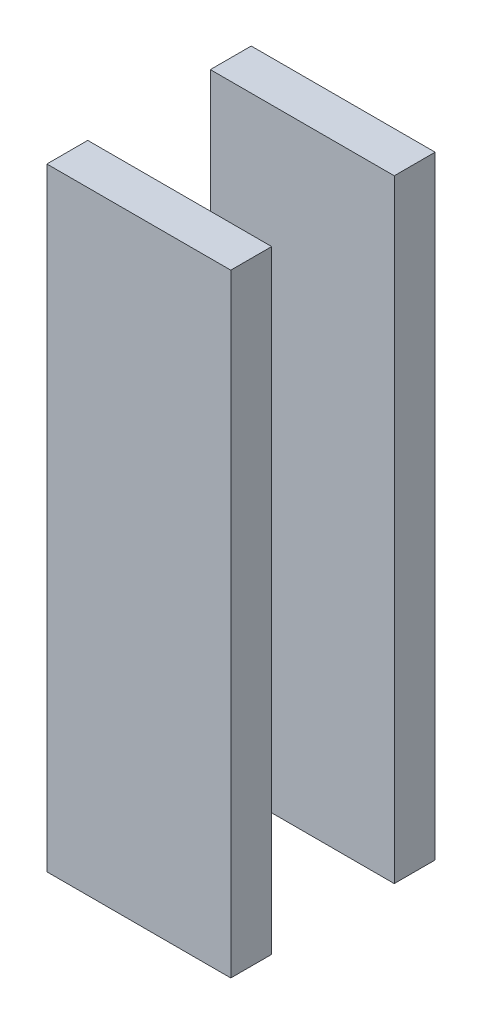
SolidWorks part; units mm, degrees
ref_plane "前视基准面" through (0, 0, 0) normal (0, 0, 1) x (1, 0, 0)
ref_plane "上视基准面" through (0, 0, 0) normal (0, 1, 0) x (1, 0, 0)
ref_plane "右视基准面" through (0, 0, 0) normal (1, 0, 0) x (0, 0, -1)
sketch "草图1" plane through (0, 0, 0) normal (0, 1, 0) x (1, 0, 0)
  line L1 (-11.5229, 45.3639) -> (33.4771, 45.3639)
  line L2 (-11.5229, 45.3639) -> (-11.5229, 35.3639)
  line L3 (-11.5229, 35.3639) -> (33.4771, 35.3639)
  line L4 (33.4771, 45.3639) -> (33.4771, 35.3639)
  line L5 (-11.5229, 5.3639) -> (33.4771, 5.3639)
  line L6 (-11.5229, 5.3639) -> (-11.5229, -4.6361)
  line L7 (-11.5229, -4.6361) -> (33.4771, -4.6361)
  line L8 (33.4771, 5.3639) -> (33.4771, -4.6361)
  dimension "D1" = 45
  dimension "D2" = 10
  dimension "D3" = 45
  dimension "D4" = 10
  dimension "D5" = 30
extrude "凸台-拉伸1" add sketch "草图1" along normal blind 150
